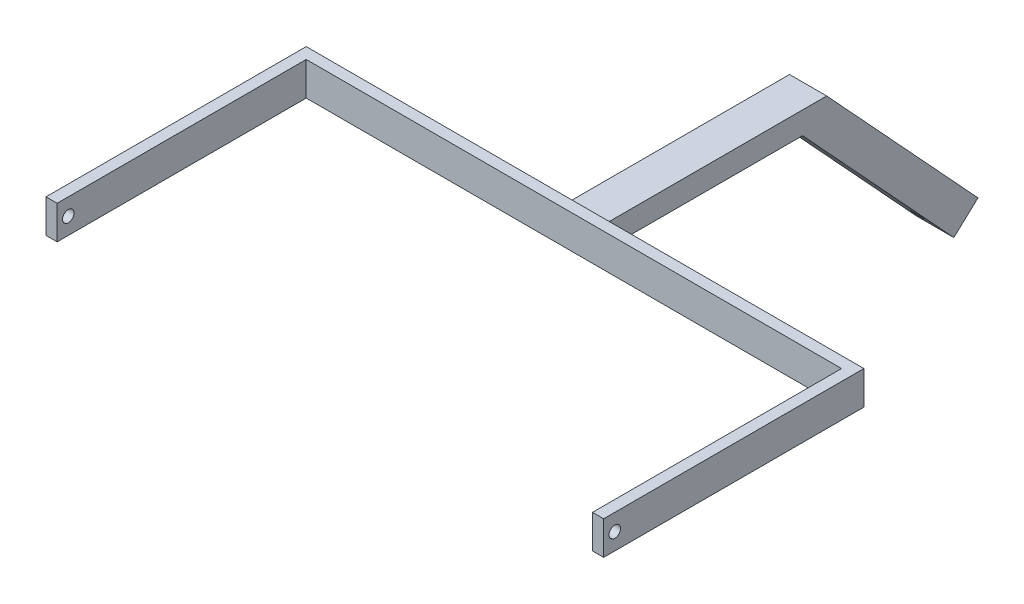
SolidWorks part; units mm, degrees
ref_plane "前视基准面" through (0, 0, 0) normal (0, 0, 1) x (1, 0, 0)
ref_plane "上视基准面" through (0, 0, 0) normal (0, 1, 0) x (1, 0, 0)
ref_plane "右视基准面" through (0, 0, 0) normal (1, 0, 0) x (0, 0, -1)
other "Configuration Table"
sketch "草图1" plane through (0, 0, 0) normal (0, 1, 0) x (1, 0, 0)
  line L0 (-72.7576, -1.4848) -> (-72.7576, -68.4848)
  line L1 (71.2424, -1.4848) -> (-72.7576, -1.4848)
  line L2 (74.2424, -1.4848) -> (74.2424, 1.5152)
  line L3 (74.2424, 1.5152) -> (-75.7576, 1.5152)
  line L4 (-75.7576, -1.4848) -> (-75.7576, 1.5152)
  line L5 (71.2424, -1.4248) -> (-75.7576, 1.5152) construction
  line L6 (74.2424, 1.5152) -> (-72.7576, -1.4848) construction
  line L7 (-75.7576, 1.5152) -> (-72.7576, 1.5152)
  line L8 (-75.7576, 1.5152) -> (-75.7576, -68.4848)
  line L9 (-75.7576, -68.4848) -> (-72.7576, -68.4848)
  line L10 (-72.7576, 1.5152) -> (-72.7576, 1.4552)
  line L11 (74.2424, 1.5152) -> (71.2424, 1.5152)
  line L12 (74.2424, 1.5152) -> (74.2424, -68.4848)
  line L13 (74.2424, -68.4848) -> (71.2424, -68.4848)
  line L14 (71.2424, 1.5152) -> (71.2424, 1.4539)
  line L15 (71.2424, -1.4248) -> (71.2424, -68.4848)
  point P0 (0, 0)
  point P12 (-72.7576, -1.4848)
  point P13 (71.2424, -1.4848)
  dimension "D1" = 150
  dimension "D2" = 3
  dimension "D3" = 3
  dimension "D4" = 70
  dimension "D5" = 70
  dimension "D6" = 3
  dimension "D7" = 67
  dimension "D8" = 67.06
  dimension "D9" = 150
  dimension "D10" = 67
extrude "凸台-拉伸2" add sketch "草图1" along normal blind 6
sketch "草图2" plane through (-72.7576, 0, 0) normal (1, 0, 0) x (0, 0, -1)
  line L0 (-68.4848, 6) -> (-68.4848, 0) construction
  line L1 (-1.4848, 0) -> (-68.4848, 0) construction
  circle A0 centre (-65.4848, 3) radius 1.55
  dimension "D2" = 3.1
  dimension "D1" = 3
  dimension "D3" = 3
extrude "切除-拉伸1" cut sketch "草图2" against normal blind 10
sketch "草图3" plane through (74.2424, 0, 0) normal (1, 0, 0) x (0, 0, -1)
  line L0 (-68.4848, 6) -> (-68.4848, 0) construction
  line L1 (1.5152, 0) -> (-68.4848, 0) construction
  circle A0 centre (-65.4848, 3) radius 1.55
  dimension "D2" = 3.1
  dimension "D1" = 3
  dimension "D3" = 3
extrude "切除-拉伸2" cut sketch "草图3" against normal blind 10 contours A0
sketch "草图5" plane through (0, 0, -1.5152) normal (0, 0, -1) x (-1, 0, 0)
  line L3 (3.7576, 0) -> (-2.2424, 0)
  line L4 (3.7576, 0) -> (3.7576, 6)
  line L5 (3.7576, 6) -> (-2.2424, 6)
  line L6 (-2.2424, 0) -> (-2.2424, 6)
  line L7 (3.7576, 0) -> (-2.2424, 6) construction
  line L8 (3.7576, 6) -> (-2.2424, 0) construction
  line L9 (75.7576, 6) -> (75.7576, 0) construction
  line L12 (-74.2424, 0) -> (75.7576, 0) construction
  point P0 (0.7576, 3)
  dimension "D3" = 6
  dimension "D1" = 75
  dimension "D2" = 3
  dimension "D4" = 6
sketch "草图6" plane through (0, 6, 0) normal (0, 1, 0) x (1, 0, 0)
  line L0 (-75.7576, 1.5152) -> (74.2424, 1.5152)
  line L1 (74.2424, 1.5152) -> (74.2424, -68.4848)
  line L2 (74.2424, -68.4848) -> (71.2424, -68.4848)
  line L3 (71.2424, -68.4848) -> (71.2424, -1.4848)
  line L4 (71.2424, -1.4848) -> (-72.7576, -1.4848)
  line L5 (-72.7576, -1.4848) -> (-72.7576, -68.4848)
  line L6 (-72.7576, -68.4848) -> (-75.7576, -68.4848)
  line L7 (-75.7576, -68.4848) -> (-75.7576, 1.5152)
extrude "凸台-拉伸4" add sketch "草图6" along normal blind 1.5
sketch "草图7" plane through (0, 0, 0) normal (0, -1, 0) x (1, 0, 0)
  line L0 (-75.7576, 68.4848) -> (-75.7576, -1.5152)
  line L1 (-75.7576, -1.5152) -> (74.2424, -1.5152)
  line L2 (74.2424, -1.5152) -> (74.2424, 68.4848)
  line L3 (74.2424, 68.4848) -> (71.2424, 68.4848)
  line L4 (71.2424, 68.4848) -> (71.2424, 1.4848)
  line L5 (71.2424, 1.4848) -> (-72.7576, 1.4848)
  line L6 (-72.7576, 1.4848) -> (-72.7576, 68.4848)
  line L7 (-72.7576, 68.4848) -> (-75.7576, 68.4848)
extrude "凸台-拉伸5" add sketch "草图7" along normal blind 1.5
extrude "凸台-拉伸6" add sketch "草图5" along normal blind 60 contours L5 L6 L3 L4
sketch "草图8" plane through (2.2424, 0, 0) normal (1, 0, 0) x (0, 0, -1)
  line L0 (61.5152, 6) -> (55.0152, 0)
  line L1 (61.5152, 0) -> (1.5152, 0) construction
  line L2 (55.0152, 0) -> (61.5152, 0)
  line L3 (61.5152, 0) -> (61.5152, 6)
  dimension "D1" = 6.5
extrude "切除-拉伸3" cut sketch "草图8" against normal blind 60
sketch "草图9" plane through (0, -27.4197, -25.3105) normal (0, -0.7348, -0.6783) x (1, 0, 0)
  line L0 (-3.7576, -40.4253) -> (-3.7576, -49.2712)
  line L1 (-3.7576, -49.2712) -> (2.2424, -49.2712)
  line L2 (2.2424, -49.2712) -> (2.2424, -40.4253)
  line L3 (2.2424, -40.4253) -> (-3.7576, -40.4253)
extrude "凸台-拉伸7" add sketch "草图9" along normal blind 60
sketch "草图10" plane through (0, -71.5079, -66.0073) normal (0, -0.7348, -0.6783) x (1, 0, 0)
  line L0 (-3.7576, -40.4253) -> (2.2424, -49.2712) construction
  line L1 (-3.7576, -49.2712) -> (2.2424, -40.4253) construction
  line L3 (1.7424, -46.8483) -> (-3.2576, -46.8483)
  line L4 (1.7424, -46.8483) -> (1.7424, -42.8483)
  line L5 (1.7424, -42.8483) -> (-3.2576, -42.8483)
  line L6 (-3.2576, -46.8483) -> (-3.2576, -42.8483)
  line L7 (1.7424, -46.8483) -> (-3.2576, -42.8483) construction
  line L8 (1.7424, -42.8483) -> (-3.2576, -46.8483) construction
  point P8 (-0.7576, -44.8483)
  point P9 (-0.7576, -44.8483)
  dimension "D1" = 4
  dimension "D2" = 5
sketch "草图11" plane through (0, 33.4197, -36.2047) normal (0, 0.6783, -0.7348) x (-1, 0, 0)
  line L0 (-2.2424, -97.3157) -> (-2.2424, -37.3157) construction
  line L1 (3.7576, -97.3157) -> (-2.2424, -97.3157)
  line L2 (3.7576, -97.3157) -> (3.7576, -87.3157)
  line L3 (3.7576, -87.3157) -> (-2.2424, -87.3157)
  line L4 (-2.2424, -97.3157) -> (-2.2424, -87.3157)
  circle A0 centre (0.7576, -90.3157) radius 1.55
  dimension "D4" = 3.1
  dimension "D1" = 10
  dimension "D2" = 3
  dimension "D3" = 3
extrude "切除-拉伸5" cut sketch "草图11" against normal blind 10 contours A0
extrude "切除-拉伸6" cut sketch "草图10" against normal blind 10
sketch "草图12" plane through (-3.7576, 0, 0) normal (-1, 0, 0) x (0, 0, 1)
  line L0 (-102.212, -38.0882) -> (-95.712, -44.0882)
  line L1 (-95.712, -44.0882) -> (-55.0152, 0)
  line L2 (-55.0152, 0) -> (-1.5152, 0)
  line L3 (-1.5152, 0) -> (-1.5152, 6)
  line L4 (-1.5152, 6) -> (-61.5152, 6)
  line L5 (-61.5152, 6) -> (-102.212, -38.0882)
extrude "凸台-拉伸8" add sketch "草图12" along normal blind 2
sketch "草图13" plane through (2.2424, 0, 0) normal (1, 0, 0) x (0, 0, -1)
  line L0 (95.712, -44.0882) -> (102.212, -38.0882)
  line L1 (102.212, -38.0882) -> (61.5152, 6)
  line L2 (61.5152, 6) -> (1.5152, 6)
  line L3 (1.5152, 6) -> (1.5152, 0)
  line L4 (1.5152, 0) -> (55.0152, 0)
  line L5 (55.0152, 0) -> (95.712, -44.0882)
extrude "凸台-拉伸9" add sketch "草图13" along normal blind 2
